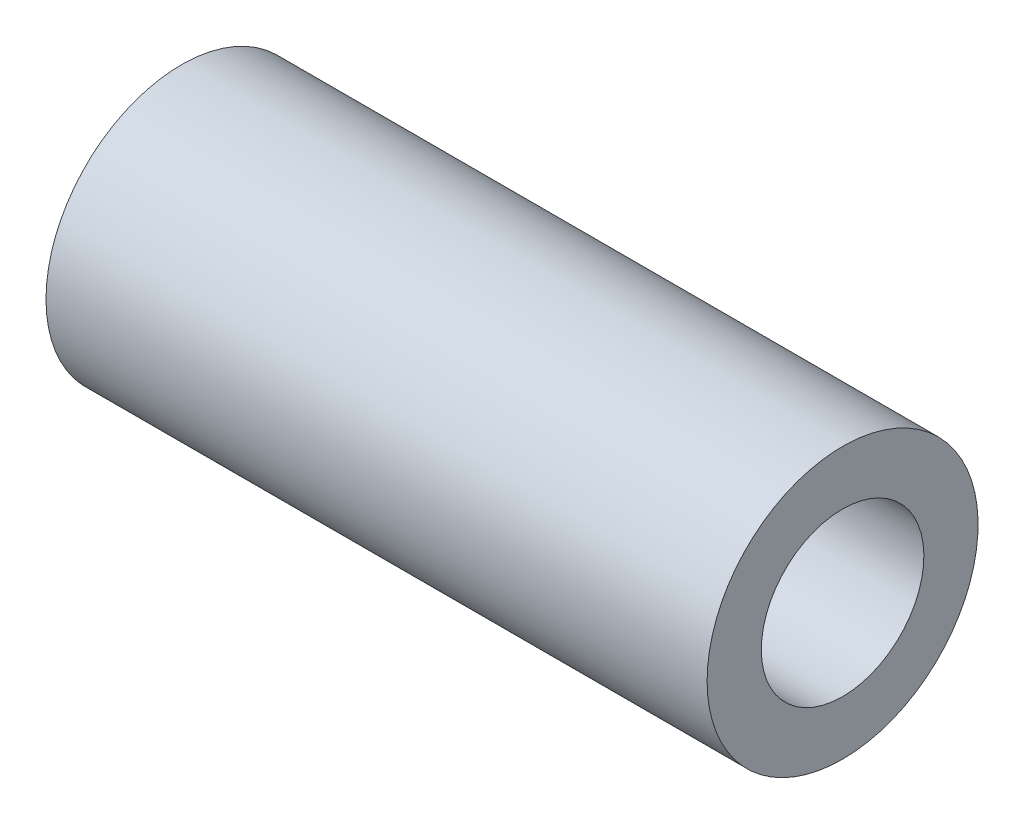
SolidWorks part; units mm, degrees
ref_plane "Front Plane" through (0, 0, 0) normal (0, 0, 1) x (1, 0, 0)
ref_plane "Top Plane" through (0, 0, 0) normal (0, 1, 0) x (1, 0, 0)
ref_plane "Right Plane" through (0, 0, 0) normal (1, 0, 0) x (0, 0, -1)
sketch "Sketch1" plane through (-0.45, 0, 0) normal (-1, 0, 0) x (0, 0, 1)
  circle A0 centre (-94.7711, 130.5312) radius 2.5
  circle A1 centre (-94.7711, 130.5312) radius 1.5
  circle A2 centre (-94.7711, 130.5312) radius 1.5 construction
  dimension "D1" = 5
extrude "Boss-Extrude1" add sketch "Sketch1" along normal up to surface (12.2 mm away)
